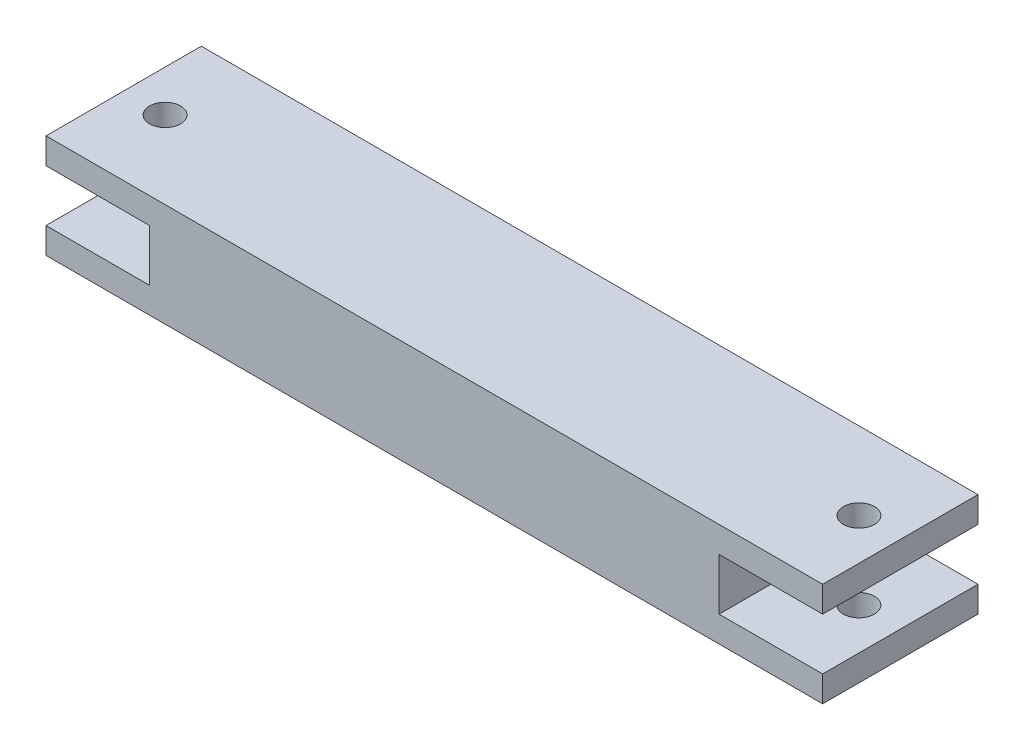
SolidWorks part; units mm, degrees
material "1060 Alloy"
ref_plane "Front Plane" through (0, 0, 0) normal (0, 0, 1) x (1, 0, 0)
ref_plane "Top Plane" through (0, 0, 0) normal (0, 1, 0) x (1, 0, 0)
ref_plane "Right Plane" through (0, 0, 0) normal (1, 0, 0) x (0, 0, -1)
sketch "Sketch1" plane through (0, 0, 0) normal (0, 1, 0) x (1, 0, 0)
  line L1 (-58.8028, 17.0775) -> (91.1972, 17.0775)
  line L2 (-58.8028, 17.0775) -> (-58.8028, -12.9225)
  line L3 (-58.8028, -12.9225) -> (91.1972, -12.9225)
  line L4 (91.1972, 17.0775) -> (91.1972, -12.9225)
  dimension "D1" = 150
  dimension "D2" = 30
extrude "Boss-Extrude1" add sketch "Sketch1" along normal blind 20
sketch "Sketch2" plane through (0, 20, 0) normal (0, 1, 0) x (1, 0, 0)
  line L0 (-58.8028, 17.0775) -> (-58.8028, -12.9225) construction
  line L2 (16.1972, 17.0775) -> (16.1972, -12.9225) construction
  line L3 (91.1972, 17.0775) -> (-58.8028, 17.0775) construction
  line L4 (-58.8028, -12.9225) -> (91.1972, -12.9225) construction
  circle A0 centre (-50.8028, 2.0775) radius 3
  circle A1 centre (83.1972, 2.0775) radius 3
  dimension "D1" = 6
  dimension "D2" = 8
extrude "Cut-Extrude1" cut sketch "Sketch2" against normal blind 20
sketch "Sketch3" plane through (-58.8028, 0, 0) normal (-1, 0, 0) x (0, 0, 1)
  line L0 (-17.0775, 20) -> (-17.0775, 0) construction
  line L1 (-17.0775, 15) -> (12.9225, 15)
  line L2 (-17.0775, 15) -> (-17.0775, 5)
  line L3 (-17.0775, 5) -> (12.9225, 5)
  line L4 (12.9225, 15) -> (12.9225, 5)
  line L5 (12.9225, 20) -> (12.9225, 0) construction
  line L7 (-17.0775, 20) -> (12.9225, 20) construction
  dimension "D1" = 10
  dimension "D2" = 5
extrude "Cut-Extrude2" cut sketch "Sketch3" against normal blind 20
sketch "Sketch4" plane through (91.1972, 0, 0) normal (1, 0, 0) x (0, 0, -1)
  line L0 (-12.9225, 20) -> (-12.9225, 0) construction
  line L1 (-12.9225, 15) -> (17.0775, 15)
  line L2 (-12.9225, 15) -> (-12.9225, 5)
  line L3 (-12.9225, 5) -> (17.0775, 5)
  line L4 (17.0775, 15) -> (17.0775, 5)
  line L5 (17.0775, 20) -> (17.0775, 0) construction
  line L6 (-12.9225, 20) -> (17.0775, 20) construction
  dimension "D1" = 10
  dimension "D2" = 5
extrude "Cut-Extrude3" cut sketch "Sketch4" against normal blind 20
ref_plane "Plane1" through (16.1972, 0, 0) normal (-1, 0, 0) x (0, 0, 1)
